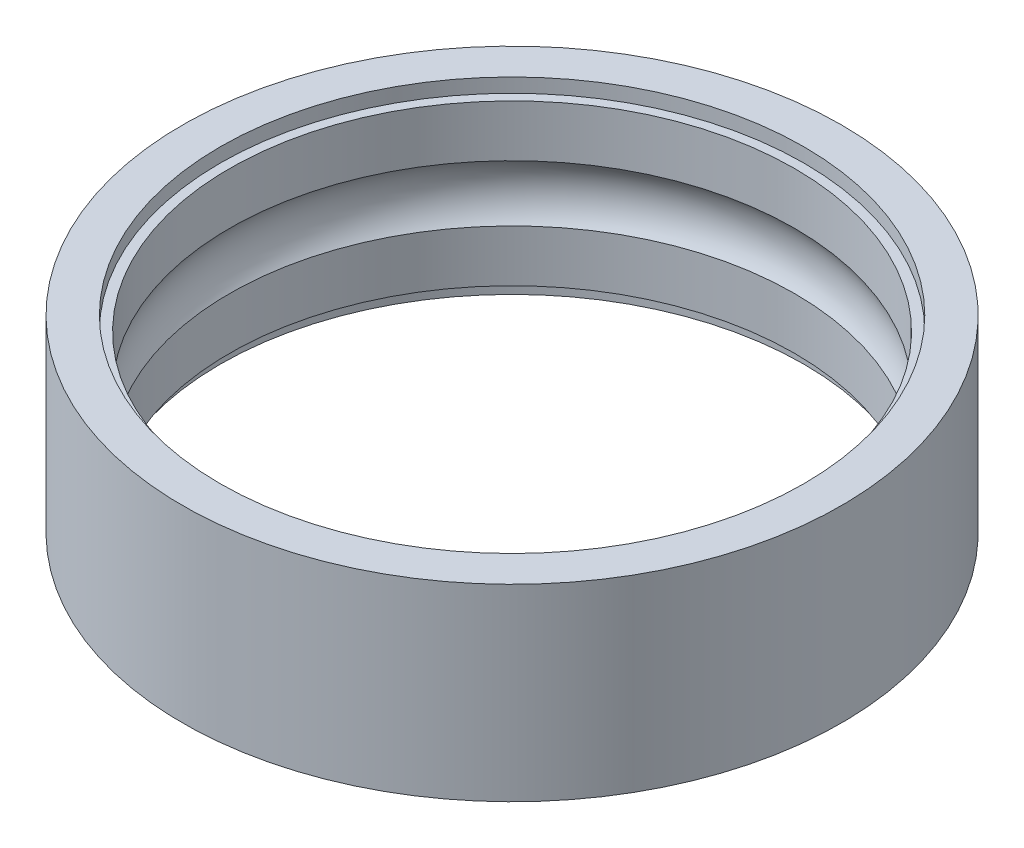
SolidWorks part; units mm, degrees
ref_plane "Front Plane" through (0, 0, 0) normal (0, 0, 1) x (1, 0, 0)
ref_plane "Top Plane" through (0, 0, 0) normal (0, 1, 0) x (1, 0, 0)
ref_plane "Right Plane" through (0, 0, 0) normal (1, 0, 0) x (0, 0, -1)
sketch "Sketch1" plane through (0, 0, 0) normal (0, 0, 1) x (1, 0, 0)
  line L0 (0, 0) -> (10.5, 0) construction
  line L1 (0, 0) -> (0, 10443.8576) construction
  line L2 (15, 4.25) -> (15, 1.5)
  line L3 (15.4962, -5) -> (17.5, -5)
  line L4 (13, -5) -> (13, -2.5) construction
  line L5 (15.4962, 5) -> (17.5, 5)
  line L6 (17.5, -5) -> (17.5, 5)
  line L7 (13, -5) -> (14.285, -2.1445) construction
  line L8 (13, 5) -> (17.5, -5) construction
  line L9 (10.5, 0) -> (13, 0) construction
  line L10 (13, 0) -> (10443.8576, 0) construction
  line L11 (13, -2.5) -> (13, 0) construction
  line L12 (13, 2.5) -> (13, 5) construction
  line L13 (13, 0) -> (13, 2.5) construction
  line L14 (15, 0) -> (15, -0.5556) construction
  line L15 (15, -1.5) -> (15, -4.25)
  line L16 (15, 0.5556) -> (15, 0) construction
  line L17 (15, -0.5556) -> (15, -1.5) construction
  line L18 (14.285, -2.1445) -> (15, -0.5556) construction
  line L19 (15, -0.5556) -> (17.5, 5) construction
  line L20 (15, 1.5) -> (15, 0.5556) construction
  line L21 (13, 5) -> (15, 5) construction
  line L22 (13, -5) -> (15, -5) construction
  line L23 (15, 4.25) -> (15.4962, 4.25)
  line L24 (15.4962, 4.25) -> (15.4962, 5)
  line L25 (15, -4.25) -> (15.4962, -4.25)
  line L26 (15.4962, -4.25) -> (15.4962, -5)
  line L27 (15, 5) -> (15.4962, 5) construction
  line L28 (15, 5) -> (15, 4.25) construction
  line L29 (15, -4.25) -> (15, -5) construction
  line L30 (15, -5) -> (15.4962, -5) construction
  arc A0 (15, -1.5) -> (15, 1.5) centre (13, 0) ccw
  arc A1 (13, 2.5) -> (10.5, 0) centre (13, 0) ccw construction
  arc A2 (10.5, 0) -> (13, -2.5) centre (13, 0) ccw construction
  arc A3 (13, -2.5) -> (14.285, -2.1445) centre (13, 0) ccw construction
  arc A4 (14.285, 2.1445) -> (13, 2.5) centre (13, 0) ccw construction
  arc A5 (14.285, -2.1445) -> (15, -1.5) centre (13, 0) ccw construction
  arc A6 (15, 1.5) -> (14.285, 2.1445) centre (13, 0) ccw construction
  point P5 (15.25, 0)
  dimension "D4" = 5
  dimension "D1" = 13
  dimension "D2" = 4.5
  dimension "D3" = 10
  dimension "D5" = 2
  dimension "D6" = 0.75
  dimension "D7" = 0.4962
revolve "Revolve1" add sketch "Sketch1" angle 360 about L1
